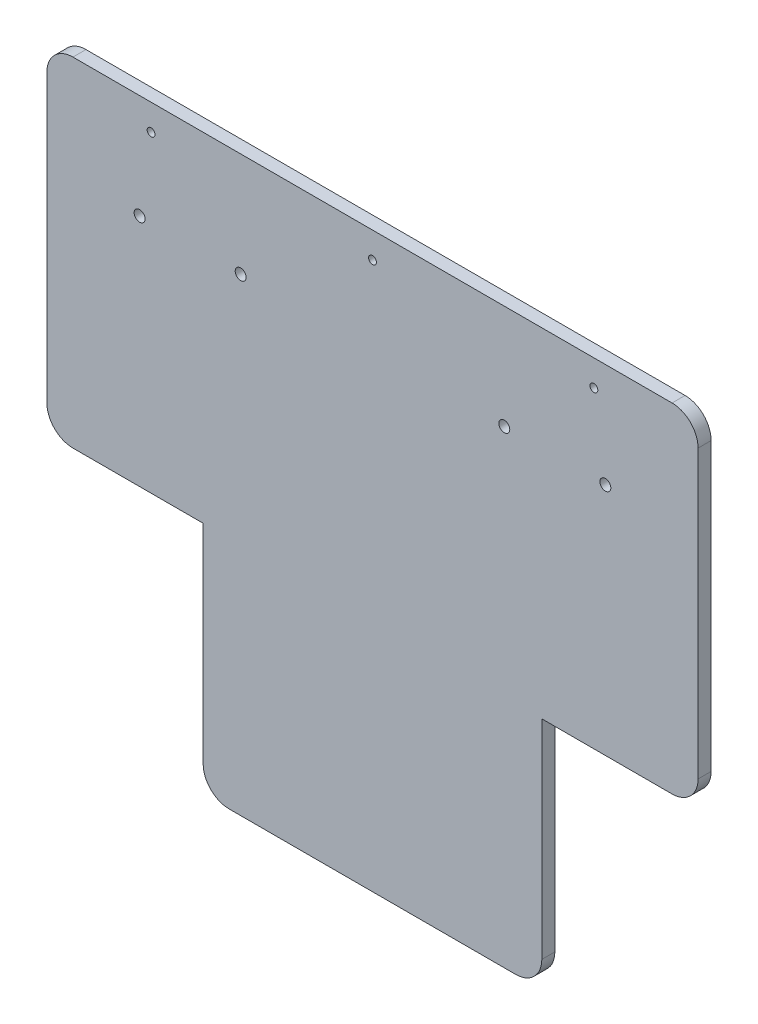
SolidWorks part; units mm, degrees
ref_plane "前视基准面" through (0, 0, 0) normal (0, 0, 1) x (1, 0, 0)
ref_plane "上视基准面" through (0, 0, 0) normal (0, 1, 0) x (1, 0, 0)
ref_plane "右视基准面" through (0, 0, 0) normal (1, 0, 0) x (0, 0, -1)
sketch "草图1" plane through (0, 0, 0) normal (0, 0, 1) x (1, 0, 0)
  line L1 (10, 0) -> (240, 0)
  line L2 (0, -10) -> (0, -210)
  line L3 (10, -220) -> (240, -220)
  line L4 (250, -10) -> (250, -210)
  arc A0 (0, -210) -> (10, -220) centre (10, -210) ccw
  arc A1 (240, -220) -> (250, -210) centre (240, -210) ccw
  arc A2 (240, 0) -> (250, -10) centre (240, -10) cw
  arc A3 (10, 0) -> (0, -10) centre (10, -10) ccw
  point P9 (250, -220)
  point P12 (250, 0)
  point P15 (0, 0)
  dimension "D3" = 10
  dimension "D1" = 250
  dimension "D2" = 220
extrude "凸台-拉伸1" add sketch "草图1" along normal blind 5
sketch "草图7" plane through (0, 0, 0) normal (0, 0, -1) x (-1, 0, 0)
  line L0 (-35.6, -40) -> (0, -40) construction
  line L1 (0, -10) -> (0, -210) construction
  line L2 (-35.6, -40) -> (-35.6, -64.4792) construction
  line L3 (-74.4, -40) -> (-74.4, -67.314) construction
  line L6 (-125, 0) -> (-125, -220) construction
  line L7 (-240, 0) -> (-10, 0) construction
  line L8 (-10, -220) -> (-240, -220) construction
  circle A0 centre (-74.4, -40) radius 2.1 construction
  circle A1 centre (-74.4, -40) radius 2.1
  circle A2 centre (-35.6, -40) radius 2.1 construction
  circle A3 centre (-35.6, -40) radius 2.1
  circle A4 centre (-214.4, -40) radius 2.1
  circle A5 centre (-175.6, -40) radius 2.1
sketch "草图9" plane through (0, 0, 5) normal (0, 0, 1) x (1, 0, 0)
  circle A0 centre (40, -10) radius 1.5 construction
  circle A1 centre (40, -10) radius 1.5
  circle A2 centre (125, -10) radius 1.5 construction
  circle A3 centre (125, -10) radius 1.5
  circle A4 centre (210, -10) radius 1.5 construction
  circle A5 centre (210, -10) radius 1.5
extrude "切除-拉伸7" cut sketch "草图9" against normal up to surface (5 mm away) up to face at (125, -110, 0)
extrude "切除-拉伸8" cut sketch "草图7" against normal up to surface (5 mm away) up to face at (41.5, -10, 5)
sketch "草图10" plane through (0, 0, 5) normal (0, 0, 1) x (1, 0, 0)
  line L0 (250, -210) -> (250, -10) construction
  line L1 (250, -130) -> (190, -130)
  line L2 (250, -130) -> (250, -220)
  line L3 (250, -220) -> (190, -220)
  line L4 (190, -130) -> (190, -220)
  line L5 (10, -220) -> (240, -220) construction
  line L6 (125, 0) -> (125, -235.6988) construction
  line L7 (240, 0) -> (10, 0) construction
  line L8 (60, -130) -> (60, -220)
  line L9 (0, -220) -> (60, -220)
  line L10 (0, -130) -> (0, -220)
  line L11 (0, -130) -> (60, -130)
  dimension "D1" = 60
  dimension "D2" = 90
extrude "切除-拉伸9" cut sketch "草图10" against normal up to next
sketch "草图11" plane through (0, 0, 5) normal (0, 0, 1) x (1, 0, 0)
  line L0 (60, -210) -> (60, -220)
  line L1 (60, -220) -> (70, -220)
  line L2 (190, -210) -> (190, -220)
  line L3 (190, -130) -> (190, -220) construction
  line L4 (60, -220) -> (190, -220) construction
  line L5 (190, -220) -> (180, -220)
  line L6 (0, -120) -> (0, -130)
  line L7 (0, -130) -> (10, -130)
  line L8 (190, -220) -> (190, -130)
  line L9 (190, -130) -> (250, -130)
  line L10 (250, -130) -> (250, -10)
  line L11 (240, 0) -> (10, 0)
  line L12 (0, -10) -> (0, -130)
  line L13 (0, -130) -> (60, -130)
  line L14 (60, -130) -> (60, -220)
  line L15 (60, -220) -> (190, -220)
  line L16 (190, -210) -> (190, -130)
  line L17 (190, -130) -> (240, -130)
  line L18 (250, -120) -> (250, -10)
  line L19 (240, 0) -> (10, 0)
  line L20 (0, -10) -> (0, -120)
  line L21 (10, -130) -> (60, -130)
  line L22 (60, -130) -> (60, -210)
  line L23 (70, -220) -> (180, -220)
  line L24 (250, -120) -> (250, -130)
  line L25 (250, -130) -> (240, -130)
  arc A0 (190, -210) -> (180, -220) centre (180, -210) cw
  arc A1 (60, -210) -> (70, -220) centre (70, -210) ccw
  arc A2 (250, -10) -> (240, 0) centre (240, -10) ccw
  arc A3 (10, 0) -> (0, -10) centre (10, -10) ccw
  arc A4 (250, -10) -> (240, 0) centre (240, -10) ccw
  arc A5 (10, 0) -> (0, -10) centre (10, -10) ccw
  arc A6 (240, -130) -> (250, -120) centre (240, -120) ccw
  arc A7 (0, -120) -> (10, -130) centre (10, -120) ccw
  line M11 (190, -220) -> (190, -130)
  line M12 (190, -130) -> (250, -130)
  line M13 (250, -130) -> (250, -10)
  line M17 (0, -10) -> (0, -130)
  line M18 (0, -130) -> (60, -130)
  line M19 (60, -130) -> (60, -220)
  line M20 (60, -220) -> (190, -220)
  dimension "D2" = 10
  dimension "D3" = 10
  dimension "D1" = 0
extrude "切除-拉伸11" cut sketch "草图11" against normal up to next contours A7 M17 M18 | A1 M19 M20 | A0 M11 M20 | A6 M12 M13
